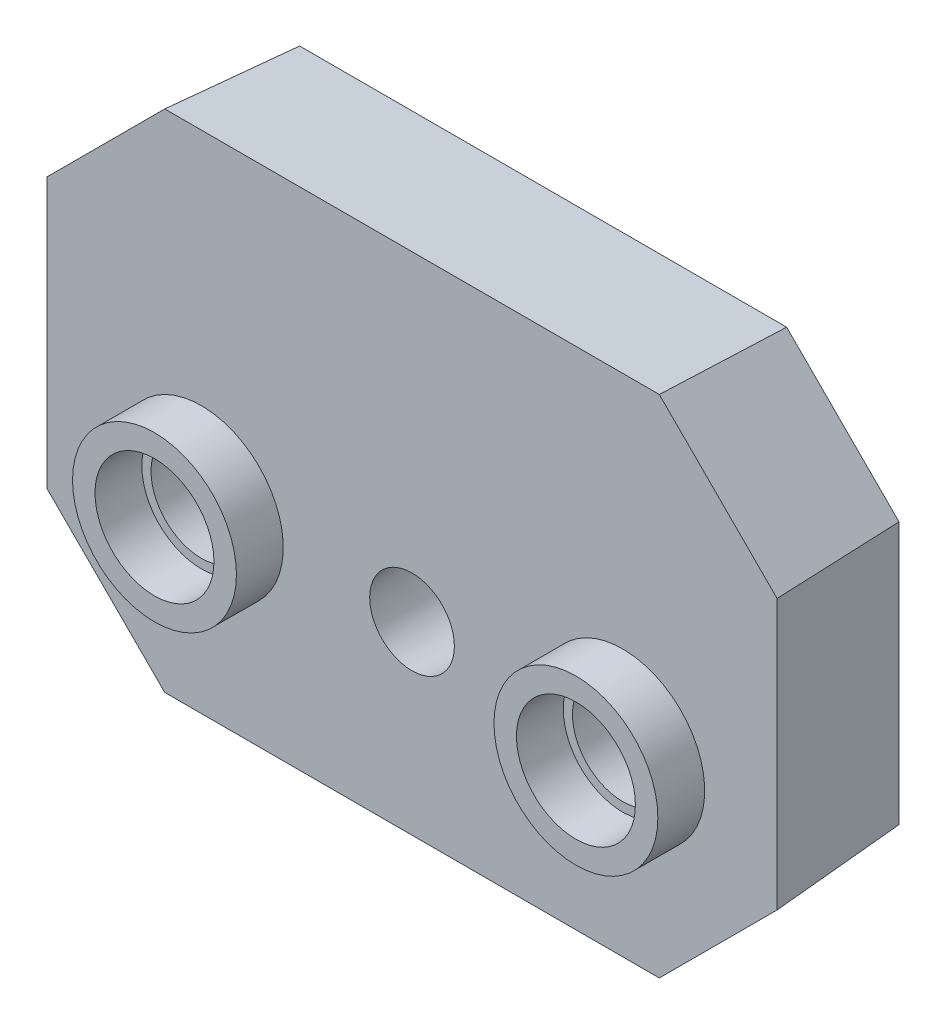
SolidWorks part; units mm, degrees
ref_plane "Front Plane" through (0, 0, 0) normal (0, 0, 1) x (1, 0, 0)
ref_plane "Top Plane" through (0, 0, 0) normal (0, 1, 0) x (1, 0, 0)
ref_plane "Right Plane" through (0, 0, 0) normal (1, 0, 0) x (0, 0, -1)
sketch "Sketch1" plane through (0, 0, 0) normal (0, 0, 1) x (1, 0, 0)
  line L0 (-52, 52) -> (52, 52)
  line L1 (52, 52) -> (76, 28)
  line L2 (76, 28) -> (76, -28)
  line L3 (76, -28) -> (52, -52)
  line L4 (52, -52) -> (-52, -52)
  line L5 (-52, -52) -> (-76, -28)
  line L6 (-76, -28) -> (-76, 28)
  line L7 (-76, 28) -> (-52, 52)
  circle A0 centre (-45, -14.5) radius 12.7
  circle A1 centre (45, -14.5) radius 12.7
  circle A2 centre (0, -14.5) radius 11
extrude "Boss-Extrude1" add sketch "Sketch1" along normal blind 28 draft 4 draft outward yes
sketch "Sketch2" plane through (0, 0, 0) normal (0, 0, 1) x (1, 0, 0)
  circle A0 centre (-45, -14.5) radius 17.5
  circle A1 centre (-45, -14.5) radius 12.7
  circle A2 centre (45, -14.5) radius 17.5
  circle A3 centre (45, -14.5) radius 12.7
extrude "Boss-Extrude2" add sketch "Sketch2" along normal blind 38
